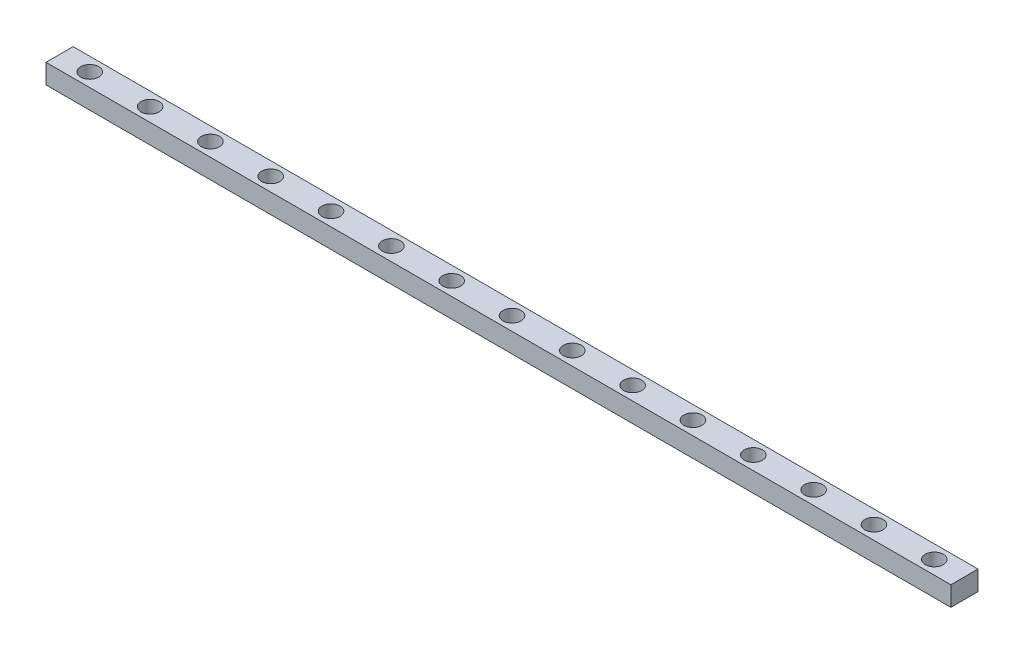
SolidWorks part; units mm, degrees
ref_plane "Front Plane" through (0, 0, 0) normal (0, 0, 1) x (1, 0, 0)
ref_plane "Top Plane" through (0, 0, 0) normal (0, 1, 0) x (1, 0, 0)
ref_plane "Right Plane" through (0, 0, 0) normal (1, 0, 0) x (0, 0, -1)
sketch "Sketch1" plane through (0, 0, 0) normal (1, 0, 0) x (0, 0, -1)
  line L1 (-4.5, 3.25) -> (4.5, 3.25)
  line L2 (-4.5, 3.25) -> (-4.5, -3.25)
  line L3 (-4.5, -3.25) -> (4.5, -3.25)
  line L4 (4.5, 3.25) -> (4.5, -3.25)
  line L5 (-4.5, 3.25) -> (4.5, -3.25) construction
  line L6 (-4.5, -3.25) -> (4.5, 3.25) construction
  point P0 (0, 0)
  dimension "D1" = 9
  dimension "D2" = 6.5
extrude "Boss-Extrude1" add sketch "Sketch1" along normal mid plane 300
sketch "Sketch2" plane through (0, 3.25, 0) normal (0, 1, 0) x (1, 0, 0)
  circle A0 centre (0, 0) radius 1.75
  dimension "D2" = 3.5
extrude "Cut-Extrude1" cut sketch "Sketch2" against normal through all
sketch "Sketch3" plane through (0, 3.25, 0) normal (0, 1, 0) x (1, 0, 0)
  circle A1 centre (0, 0) radius 3
  dimension "D1" = 6
extrude "Cut-Extrude2" cut sketch "Sketch3" against normal blind 4.5
ref_plane "Plane-Center" through (0, 0, 0) normal (-1, 0, 0) x (0, 0, 1)
pattern_linear "LPattern1" count 8 spacing 20 along (-1, 0, 0) count 8 spacing 20 along (1, 0, 0) of "Cut-Extrude1", "Cut-Extrude2"
